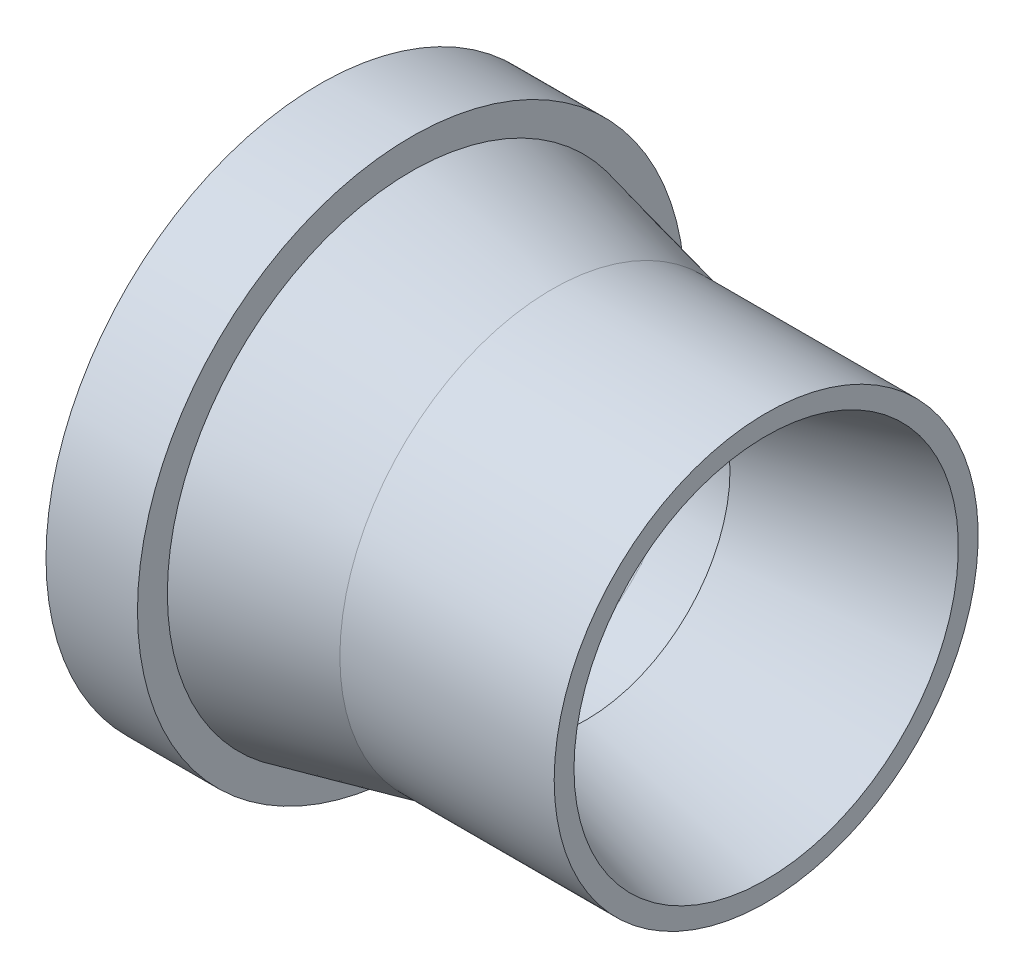
SolidWorks part; units mm, degrees
ref_plane "Front Plane" through (0, 0, 0) normal (0, 0, 1) x (1, 0, 0)
ref_plane "Top Plane" through (0, 0, 0) normal (0, 1, 0) x (1, 0, 0)
ref_plane "Right Plane" through (0, 0, 0) normal (1, 0, 0) x (0, 0, -1)
sketch "Sketch1" plane through (0, 0, 0) normal (0, 0, 1) x (1, 0, 0)
  line L0 (0, 0) -> (75.0218, 0) construction
  line L1 (0, 0) -> (0, 34.798) construction
  line L2 (0, 34.798) -> (11.6269, 34.798) construction
  line L3 (0, 34.798) -> (12.0584, 22.7396)
  line L5 (33.8433, 18.2926) -> (56.7358, 24.4266)
  line L6 (0, 34.798) -> (11.6269, 34.798)
  line L7 (11.6269, 34.798) -> (11.6269, 31.0015)
  line L8 (11.6269, 31.0015) -> (29.4966, 26.9446)
  line L9 (29.4966, 26.9446) -> (56.7358, 26.9446)
  line L10 (56.7358, 26.9446) -> (56.7358, 24.4266)
  line L16 (12.0584, 22.7396) -> (16.7464, 22.7396)
  line L17 (16.7464, 22.7396) -> (25.1844, 20.535)
  line L18 (25.1844, 20.535) -> (33.8433, 20.535)
  line L19 (33.8433, 20.535) -> (33.8433, 18.2926)
  dimension "D1" = 34.798
  dimension "D2" = 45
revolve "Revolve1" add sketch "Sketch1" angle 360 about L0
